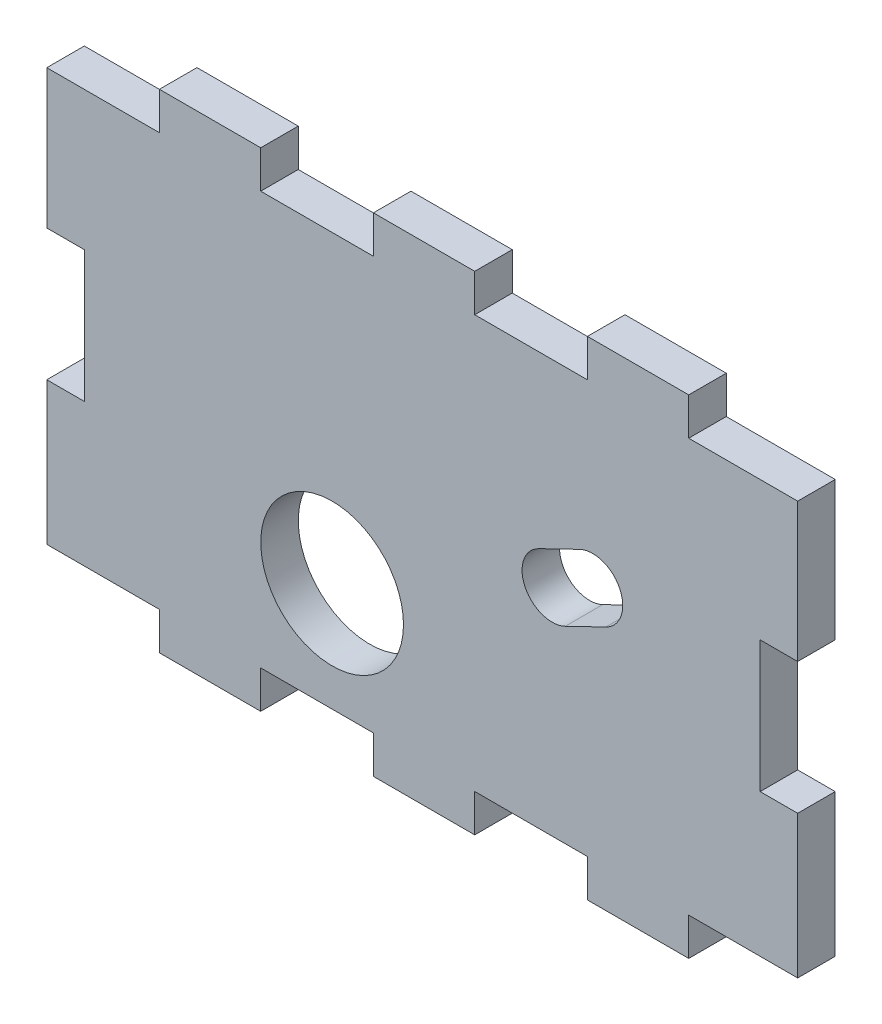
SolidWorks part; units mm, degrees
material "Acrylique (impact moyen-haut)"
ref_plane "Plan de face" through (0, 0, 0) normal (0, 0, 1) x (1, 0, 0)
ref_plane "Plan de dessus" through (0, 0, 0) normal (0, 1, 0) x (1, 0, 0)
ref_plane "Plan de droite" through (0, 0, 0) normal (1, 0, 0) x (0, 0, -1)
sketch "Esquisse1" plane through (0, 0, 0) normal (0, 0, 1) x (1, 0, 0)
  line L1 (50, -32.5) -> (-50, -32.5)
  line L2 (50, -32.5) -> (50, 32.5)
  line L3 (50, 32.5) -> (-50, 32.5)
  line L4 (-50, -32.5) -> (-50, 32.5)
  line L5 (50, -32.5) -> (-50, 32.5) construction
  line L6 (50, 32.5) -> (-50, -32.5) construction
  point P0 (0, 0)
  dimension "D1" = 100
  dimension "D2" = 65
extrude "Boss.-Extru.1" add sketch "Esquisse1" along normal blind 5
sketch "Esquisse2" plane through (0, 0, 5) normal (0, 0, 1) x (1, 0, 0)
  line L0 (50, 32.5) -> (-50, 32.5) construction
  line L1 (-50, 32.5) -> (-50, -32.5) construction
  line L2 (50, -32.5) -> (50, 32.5) construction
  line L3 (-35, 32.5) -> (-50, 32.5)
  line L4 (-35, 32.5) -> (-35, 27.49)
  line L5 (-35, 27.49) -> (-50, 27.49)
  line L6 (-50, 32.5) -> (-50, 27.49)
  line L7 (-21.51, 32.5) -> (-6.5, 32.5)
  line L8 (-21.51, 32.5) -> (-21.51, 27.49)
  line L9 (-21.51, 27.49) -> (-6.5, 27.49)
  line L10 (-6.5, 32.5) -> (-6.5, 27.49)
  line L11 (6.99, 32.5) -> (22, 32.5)
  line L12 (6.99, 32.5) -> (6.99, 27.49)
  line L13 (6.99, 27.49) -> (22, 27.49)
  line L14 (22, 32.5) -> (22, 27.49)
  line L15 (35.49, 32.51) -> (50, 32.51)
  line L16 (35.49, 32.51) -> (35.49, 27.5)
  line L17 (35.49, 27.5) -> (50, 27.5)
  line L18 (50, 32.51) -> (50, 27.5)
  line L19 (0, 32.5) -> (0, -35.188) construction
  line L20 (-50, 9) -> (-45, 9)
  line L21 (-50, 9) -> (-50, -8.5)
  line L22 (-50, -8.5) -> (-45, -8.5)
  line L23 (-45, 9) -> (-45, -8.5)
  line L24 (45, 9) -> (45, -8.5)
  line L25 (50, -8.5) -> (45, -8.5)
  line L26 (50, 9) -> (50, -8.5)
  line L27 (50, 9) -> (45, 9)
  line L28 (50.7693, 0) -> (-61.67, 0) construction
  line L29 (50, -32.51) -> (50, -27.5)
  line L30 (35.49, -27.5) -> (50, -27.5)
  line L31 (35.49, -32.51) -> (35.49, -27.5)
  line L32 (35.49, -32.51) -> (50, -32.51)
  line L33 (22, -32.5) -> (22, -27.49)
  line L34 (6.99, -27.49) -> (22, -27.49)
  line L35 (6.99, -32.5) -> (6.99, -27.49)
  line L36 (6.99, -32.5) -> (22, -32.5)
  line L37 (-6.5, -32.5) -> (-6.5, -27.49)
  line L38 (-21.51, -27.49) -> (-6.5, -27.49)
  line L39 (-21.51, -32.5) -> (-21.51, -27.49)
  line L40 (-21.51, -32.5) -> (-6.5, -32.5)
  line L41 (-50, -32.5) -> (-50, -27.49)
  line L42 (-35, -27.49) -> (-50, -27.49)
  line L43 (-35, -32.5) -> (-35, -27.49)
  line L44 (-35, -32.5) -> (-50, -32.5)
  point P0 (-35, 32.5)
  point P1 (-21.51, 32.5)
  point P6 (6.99, 32.5)
  point P9 (-50, 9)
  point P10 (-50, -8.5)
  point P13 (-50, 27.49)
  dimension "D1" = 15
  dimension "D2" = 13.49
  dimension "D3" = 5.01
  dimension "D4" = 13.49
  dimension "D5" = 5.01
  dimension "D6" = 43.5
  dimension "D7" = 23.5
  dimension "D8" = 17.5
  dimension "D9" = 5.01
  dimension "D10" = 5
  dimension "D11" = 72
  dimension "D12" = 13.49
  dimension "D13" = 5.01
extrude "Enlèv. mat.-Extru.1" cut sketch "Esquisse2" against normal blind 5
sketch "Esquisse3" plane through (0, 0, 5) normal (0, 0, 1) x (1, 0, 0)
  line L0 (-50, -8.5) -> (-50, -27.49) construction
  line L1 (-35, -32.5) -> (-21.51, -32.5) construction
  circle A0 centre (-12, -13) radius 9.505
  dimension "D3" = 19.01
  dimension "D1" = 38
  dimension "D2" = 19.5
extrude "Enlèv. mat.-Extru.2" cut sketch "Esquisse3" against normal blind 10
sketch "Esquisse4" plane through (0, 0, 5) normal (0, 0, 1) x (1, 0, 0)
  line L0 (50, 9) -> (50, 27.5) construction
  line L1 (22, -32.5) -> (35.49, -32.5) construction
  line L2 (-6.5, -32.5) -> (6.99, -32.5) construction
  line L3 (-50, -8.5) -> (-50, -27.49) construction
  line L4 (20, 2.5) -> (-12, -13) construction
  line L5 (22.6999, 3.8078) -> (17.3001, 1.1922) construction
  line L6 (24.4458, 0.2034) -> (19.0459, -2.4122)
  line L7 (20.9541, 7.4122) -> (15.5542, 4.7966)
  line L8 (13.2951, 1.1922) -> (13.2951, -6.7424) construction
  line L9 (17.3001, -2.8128) -> (10.3911, -2.8128) construction
  line L10 (-21.505, -13) -> (-21.505, -25.7585) construction
  line L11 (-12, -22.505) -> (-35.4465, -22.505) construction
  arc A0 (24.4458, 0.2034) -> (20.9541, 7.4122) centre (22.6999, 3.8078) ccw
  arc A1 (15.5542, 4.7966) -> (19.0459, -2.4122) centre (17.3001, 1.1922) ccw
  circle A2 centre (-12, -13) radius 9.505 construction
  point P0 (20, 2.5)
  point P5 (-11.9961, -13)
  point P15 (20, 2.5)
  point P24 (13.2951, -2.7751)
  point P31 (-21.505, -22.505)
  dimension "D6" = 6
  dimension "D1" = 30
  dimension "D2" = 35
  dimension "D3" = 19.5
  dimension "D4" = 38.0039
  dimension "D5" = 8.01
extrude "Enlèv. mat.-Extru.3" cut sketch "Esquisse4" against normal blind 10
